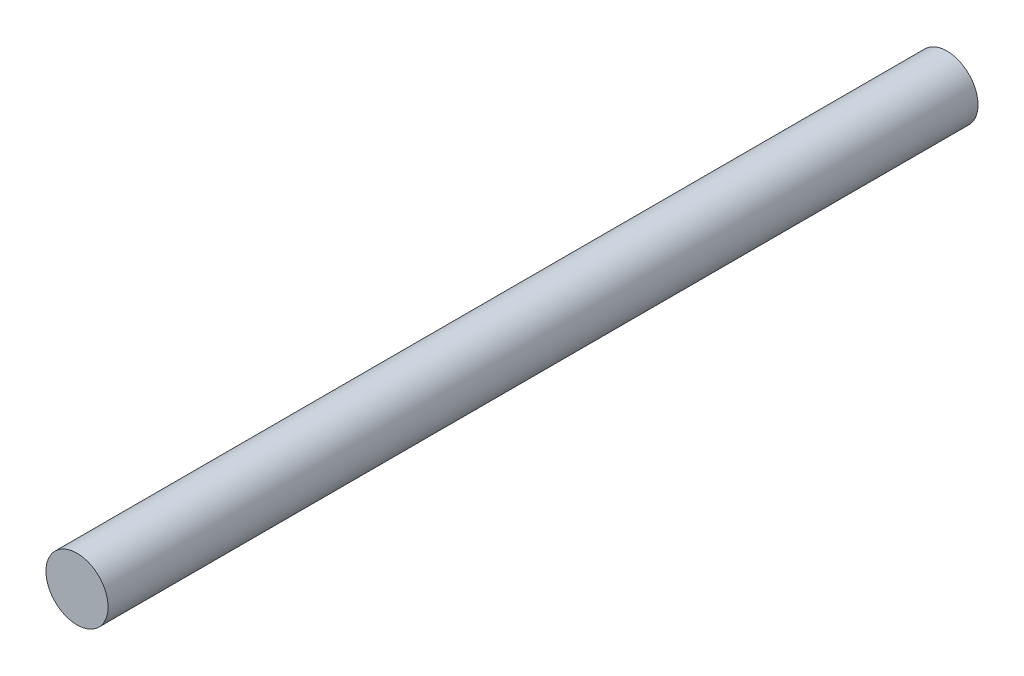
SolidWorks part; units mm, degrees
material "AISI 304"
ref_plane "Front Plane" through (0, 0, 0) normal (0, 0, 1) x (1, 0, 0)
ref_plane "Top Plane" through (0, 0, 0) normal (0, 1, 0) x (1, 0, 0)
ref_plane "Right Plane" through (0, 0, 0) normal (1, 0, 0) x (0, 0, -1)
sketch "Sketch1" plane through (0, 0, 0) normal (0, 1, 0) x (-1, 0, 0)
  line L0 (-31.5, -21) -> (-30, -21)
  line L1 (-30, -21) -> (-30, 21)
  line L2 (-30, 21) -> (-31.5, 21)
  line L3 (-31.5, 21) -> (-31.5, -21)
  line L4 (-30, -21) -> (-30, 21) construction
revolve "Revolve1" add sketch "Sketch1" angle 360 about L4
sketch "Sketch3" plane through (0, 0, 0) normal (0, 0, 1) x (1, 0, 0)
  circle A0 centre (30, 0) radius 1.5
ref_plane "Plane1" through (0, 0, 20.86) normal (0, 0, 1) x (1, 0, 0)
sketch "Sketch5" plane through (0, 0, 20.86) normal (0, 0, 1) x (1, 0, 0)
  circle A0 centre (30, 0) radius 1.5
  circle A1 centre (30, 0) radius 1.5 construction
